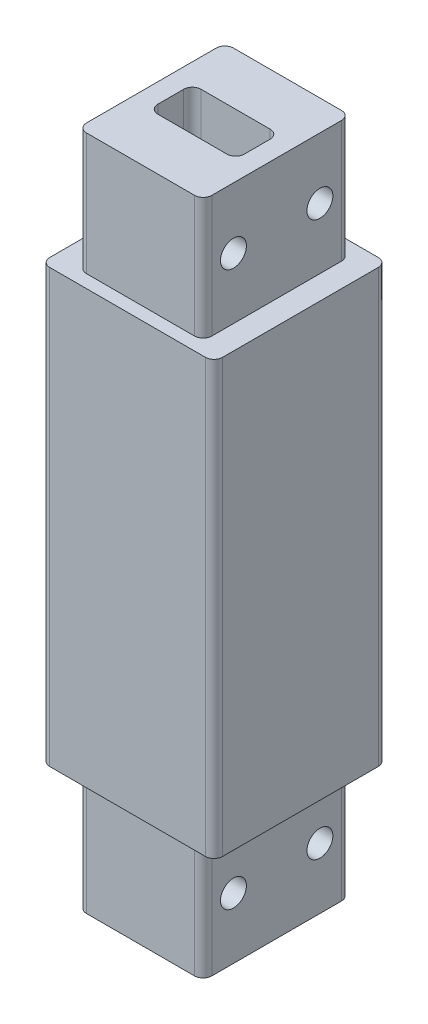
SolidWorks part; units mm, degrees
material "EVA"
ref_plane "Front Plane" through (0, 0, 0) normal (0, 0, 1) x (1, 0, 0)
ref_plane "Top Plane" through (0, 0, 0) normal (0, 1, 0) x (1, 0, 0)
ref_plane "Right Plane" through (0, 0, 0) normal (1, 0, 0) x (0, 0, -1)
sketch "Sketch1" plane through (0, 0, 0) normal (0, 1, 0) x (1, 0, 0)
  line L1 (-10, -10) -> (10, -10)
  line L2 (-10, -10) -> (-10, 10)
  line L3 (-10, 10) -> (10, 10)
  line L4 (10, -10) -> (10, 10)
  line L5 (-10, -10) -> (10, 10) construction
  line L6 (-10, 10) -> (10, -10) construction
  point P0 (0, 0)
extrude "Boss-Extrude1" add sketch "Sketch1" along normal blind 50
ref_plane "Plane1" through (0, 25, 0) normal (0, -1, 0) x (-1, 0, 0)
sketch "Sketch2" plane through (0, 25, 0) normal (0, 1, 0) x (1, 0, 0)
  line L1 (-6.25, -8.5) -> (6.25, -8.5)
  line L2 (-7.25, -7.5) -> (-7.25, 7.5)
  line L3 (-6.25, 8.5) -> (6.25, 8.5)
  line L4 (7.25, -7.5) -> (7.25, 7.5)
  line L5 (-7.25, -8.5) -> (7.25, 8.5) construction
  line L6 (-7.25, 8.5) -> (7.25, -8.5) construction
  arc A0 (6.25, -8.5) -> (7.25, -7.5) centre (6.25, -7.5) ccw
  arc A1 (-6.25, -8.5) -> (-7.25, -7.5) centre (-6.25, -7.5) cw
  arc A2 (-7.25, 7.5) -> (-6.25, 8.5) centre (-6.25, 7.5) cw
  arc A3 (6.25, 8.5) -> (7.25, 7.5) centre (6.25, 7.5) cw
  point P0 (0, 0)
  dimension "D3" = 1
  dimension "D1" = 12.5
  dimension "D2" = 15
extrude "Boss-Extrude2" add sketch "Sketch2" along normal mid plane 78.2
sketch "Sketch3" plane through (0, 64.1, 0) normal (0, 1, 0) x (1, 0, 0)
  line L1 (-4, -2.5) -> (4, -2.5)
  line L2 (-5, -1.5) -> (-5, 1.5)
  line L3 (-4, 2.5) -> (4, 2.5)
  line L4 (5, -1.5) -> (5, 1.5)
  line L5 (-5, -2.5) -> (5, 2.5) construction
  line L6 (-5, 2.5) -> (5, -2.5) construction
  arc A0 (4, -2.5) -> (5, -1.5) centre (4, -1.5) ccw
  arc A1 (-4, -2.5) -> (-5, -1.5) centre (-4, -1.5) cw
  arc A2 (-5, 1.5) -> (-4, 2.5) centre (-4, 1.5) cw
  arc A3 (4, 2.5) -> (5, 1.5) centre (4, 1.5) cw
  point P0 (0, 0)
  dimension "D3" = 1
  dimension "D1" = 5
  dimension "D2" = 10
extrude "Cut-Extrude1" cut sketch "Sketch3" against normal up to surface (14.1 mm away) up to face at (0, 50, 0)
sketch "Sketch4" plane through (0, -14.1, 0) normal (0, -1, 0) x (1, 0, 0)
  line L1 (-4, -2.5) -> (4, -2.5)
  line L2 (-5, -1.5) -> (-5, 1.5)
  line L3 (-4, 2.5) -> (4, 2.5)
  line L4 (5, -1.5) -> (5, 1.5)
  line L5 (-5, -2.5) -> (5, 2.5) construction
  line L6 (-5, 2.5) -> (5, -2.5) construction
  arc A0 (-4, -2.5) -> (-5, -1.5) centre (-4, -1.5) cw
  arc A1 (4, -2.5) -> (5, -1.5) centre (4, -1.5) ccw
  arc A2 (4, 2.5) -> (5, 1.5) centre (4, 1.5) cw
  arc A3 (-5, 1.5) -> (-4, 2.5) centre (-4, 1.5) cw
  point P0 (0, 0)
  dimension "D3" = 1
  dimension "D1" = 5
  dimension "D2" = 10
extrude "Cut-Extrude2" cut sketch "Sketch4" against normal up to surface (14.1 mm away) up to face at (0, 0, 0)
hole_wizard "M3x0.5 Tapped Hole1" positions "Sketch7" profile "Sketch9" tap size "M3x0.5" standard "ANSI Metric" end condition through all
sketch "Sketch7" plane through (7.25, 0, 0) normal (1, 0, 0) x (0, 0, -1)
  line L0 (-7.5, 50) -> (7.5, 50) construction
  line L1 (-7.5, 0) -> (7.5, 0) construction
  line L4 (-10, 50) -> (-10, 0) construction
  line L5 (10, 50) -> (10, 0) construction
  circle A0 centre (5, 57.05) radius 150
  point P0 (5, 57.05)
  point P2 (5, -7.05)
  point P11 (-5, 57.05)
  point P13 (-5, -7.05)
  dimension "D9" = 300
  dimension "D1" = 7.05
  dimension "D2" = 7.05
  dimension "D3" = 7.05
  dimension "D5" = 7.05
  dimension "D4" = 5
  dimension "D6" = 5
  dimension "D7" = 5
  dimension "D8" = 5
sketch "Sketch9" plane through (7.25, 57.05, -5) normal (0, 1, 0) x (0, 0, -1)
  line L0 (0, 0) -> (0, 17.25)
  line L1 (0, 17.25) -> (1.5, 17.25)
  line L2 (1.5, 17.25) -> (1.5, 0)
  line L5 (1.5, 0) -> (0, 0)
  line L11 (0, -6.35) -> (0, 107.95) construction
  dimension "Thread Major Dia." = 3
  dimension "Thru Tap Drill Depth" = 17.25
fillet "Fillet1" radius 1 4 edges at (10, 25, 10) (10, 25, -10) (-10, 25, 10) (-10, 25, -10)
equation "\"D2@Sketch1\"= \"t_thigh\""
equation "\"D2@Sketch2\" = \"t_thigh\" - 0.005m"
equation "\"t_thigh\"= 0.0200m"
equation "\"D4@Sketch7\"= \"t_thigh\" / 4"
equation "\"D6@Sketch7\" = \"t_thigh\" / 4"
equation "\"D7@Sketch7\" = \"t_thigh\" / 4"
equation "\"D8@Sketch7\" = \"t_thigh\" / 4"
equation "\"L_upperThigh\"= 0.2952m"
